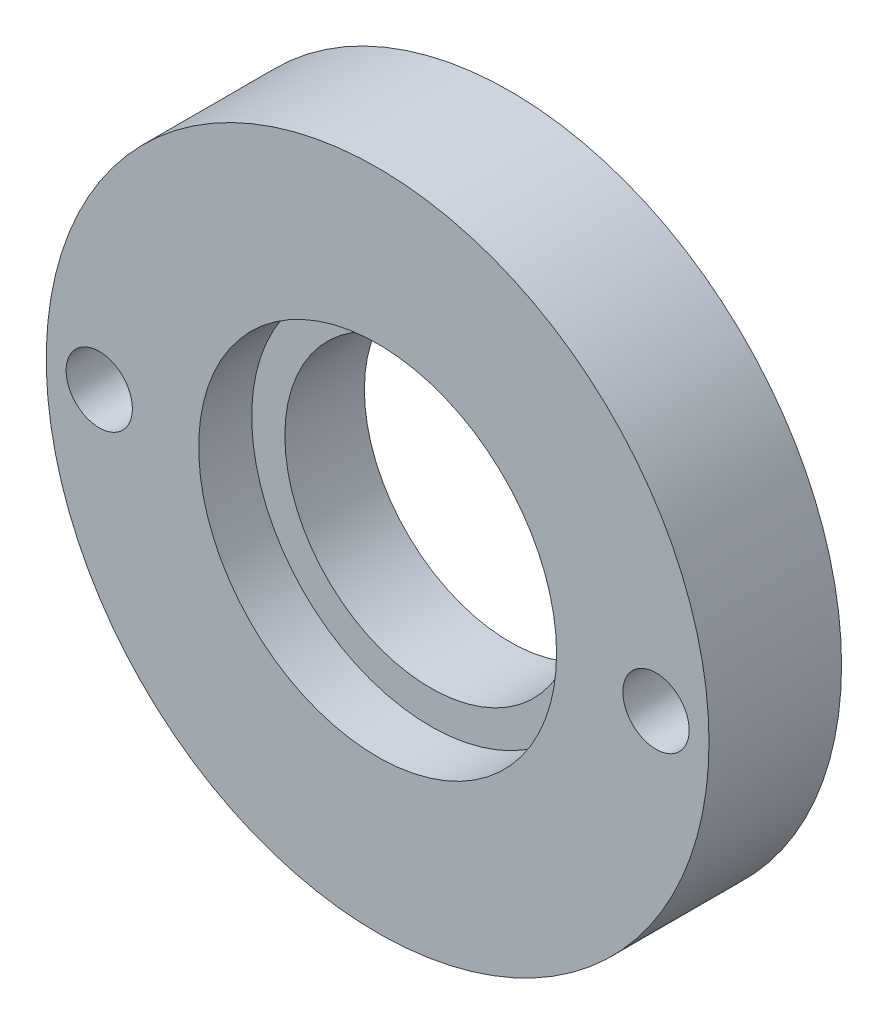
SolidWorks part; units mm, degrees
ref_plane "正面" through (0, 0, 0) normal (0, 0, 1) x (1, 0, 0)
ref_plane "平面" through (0, 0, 0) normal (0, 1, 0) x (1, 0, 0)
ref_plane "右側面" through (0, 0, 0) normal (1, 0, 0) x (0, 0, -1)
sketch "ｽｹｯﾁ1" plane through (0, 0, 0) normal (0, 0, 1) x (1, 0, 0)
  circle A0 centre (0, 0) radius 25
  dimension "D1" = 50
extrude "ﾎﾞｽ - 押し出し1" add sketch "ｽｹｯﾁ1" along normal blind 10
sketch "ｽｹｯﾁ2" plane through (0, 0, 10) normal (0, 0, 1) x (1, 0, 0)
  line L0 (0, 0) -> (21, 0) construction
  line L1 (0, 0) -> (-21, 0) construction
  circle A0 centre (0, 0) radius 13.5
  dimension "D1" = 27
  dimension "D2" = 21
  dimension "D3" = 21
extrude "ｶｯﾄ - 押し出し1" cut sketch "ｽｹｯﾁ2" against normal blind 4 contours A0
sketch "ｽｹｯﾁ4" plane through (0, 0, 0) normal (0, 0, -1) x (-1, 0, 0)
  circle A0 centre (0, 0) radius 11
  dimension "D1" = 22
extrude "ｶｯﾄ - 押し出し2" cut sketch "ｽｹｯﾁ4" against normal through all
sketch "ｽｹｯﾁ5" plane through (0, 0, 10) normal (0, 0, 1) x (1, 0, 0)
  line L0 (0, 0) -> (-21, 0) construction
  line L1 (0, 0) -> (21, 0) construction
  dimension "D1" = 21
  dimension "D2" = 21
hole_wizard "M6x1.0 ねじ穴1" positions "3Dｽｹｯﾁ1" profile "ｽｹｯﾁ6" tap size "M6x1.0" standard "JIS" end condition through all
sketch3d "3Dｽｹｯﾁ1"
  point P0 (-21, 0, 10)
  point P3 (21, 0, 10)
sketch "ｽｹｯﾁ6" plane through (-21, 0, 10) normal (1, 0, 0) x (0, -1, 0)
  line L0 (0, 0) -> (0, 10)
  line L1 (0, 10) -> (2.5, 10)
  line L2 (2.5, 10) -> (2.5, 0)
  line L5 (2.5, 0) -> (0, 0)
  line L11 (0, -6.35) -> (0, 107.95) construction
  dimension "次ｻｰﾌｪｽまでのねじ下穴ﾄﾞﾘﾙ直径" = 5
  dimension "次ｻｰﾌｪｽまでのねじ下穴ﾄﾞﾘﾙの深さ" = 10
cosmetic thread "穴のねじ山1"
cosmetic thread "穴のねじ山2"
